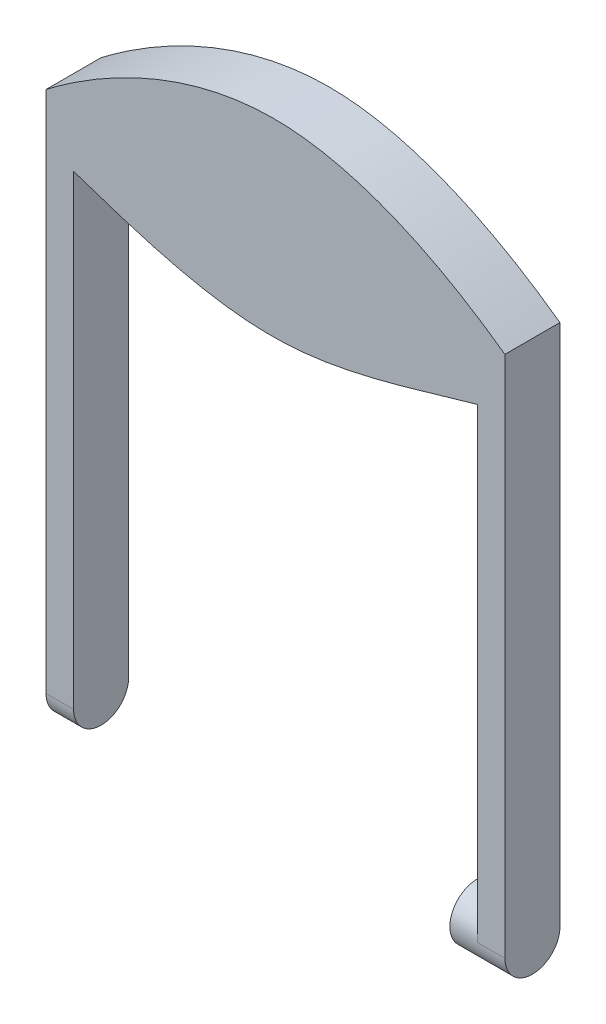
SolidWorks part; units mm, degrees
ref_plane "前视基准面" through (0, 0, 0) normal (0, 0, 1) x (1, 0, 0)
ref_plane "上视基准面" through (0, 0, 0) normal (0, 1, 0) x (1, 0, 0)
ref_plane "右视基准面" through (0, 0, 0) normal (1, 0, 0) x (0, 0, -1)
sketch "草图1" plane through (0, 0, 0) normal (0, 0, 1) x (1, 0, 0)
  line L0 (0, 0) -> (0, 60)
  line L2 (50, 60) -> (50, 0)
  line L3 (50, 0) -> (47, 0)
  line L4 (47, 0) -> (47, 53.7744)
  line L6 (3, 53.7744) -> (3, 0)
  line L7 (3, 0) -> (0, 0)
  line L8 (25, 84.5946) -> (25, -21.1964) construction
  spline S0 degree 3 poles (0, 60) (6.932, 65.3033) (25.0215, 74.1373) (42.9744, 65.0731) (50, 60) knots 0 0 0 0 0.50035 1 1 1 1
  spline S1 degree 3 poles (3, 53.7744) (9.9659, 51.4057) (25.0335, 46.4505) (39.9258, 51.8139) (47, 53.7744) knots 0 0 0 0 0.500345 1 1 1 1
  dimension "D1" = 50
  dimension "D2" = 3
  dimension "D3" = 3
  dimension "D4" = 25
extrude "凸台-拉伸1" add sketch "草图1" along normal blind 6
sketch "草图2" plane through (0, 0, 0) normal (-1, 0, 0) x (0, 0, 1)
  line L0 (6, 0) -> (0, 0) construction
  line L1 (6, 60) -> (6, 0) construction
  line L2 (6, 3) -> (6, 0)
  line L3 (6, 0) -> (3, 0)
  line L4 (3, 0) -> (0, 0)
  line L5 (0, 3) -> (0, 0)
  arc A0 (0, 3) -> (6, 3) centre (3, 3) ccw
  line M2 (0, 60) -> (0, 0)
  line M3 (0, 0) -> (6, 0)
  line M4 (6, 0) -> (6, 60)
  dimension "D1" = 6
extrude "切除-拉伸1" cut sketch "草图2" against normal through all both and the other way through all contours A0 M2 M3 | A0 M3 M4
sketch "草图3" plane through (47, 0, 0) normal (-1, 0, 0) x (0, 0, 1)
  arc A0 (0, 3) -> (6, 3) centre (3, 3) ccw construction
  arc A1 (0, 3) -> (6, 3) centre (3, 3) ccw
  circle A2 centre (3, 3) radius 3
  circle A3 centre (3, 3) radius 2.05
  arc M1 (0, 3) -> (6, 3) centre (3, 3) ccw
  dimension "D1" = 4.1
extrude "凸台-拉伸2" add sketch "草图3" along normal blind 3 contours A2 A3 M1
